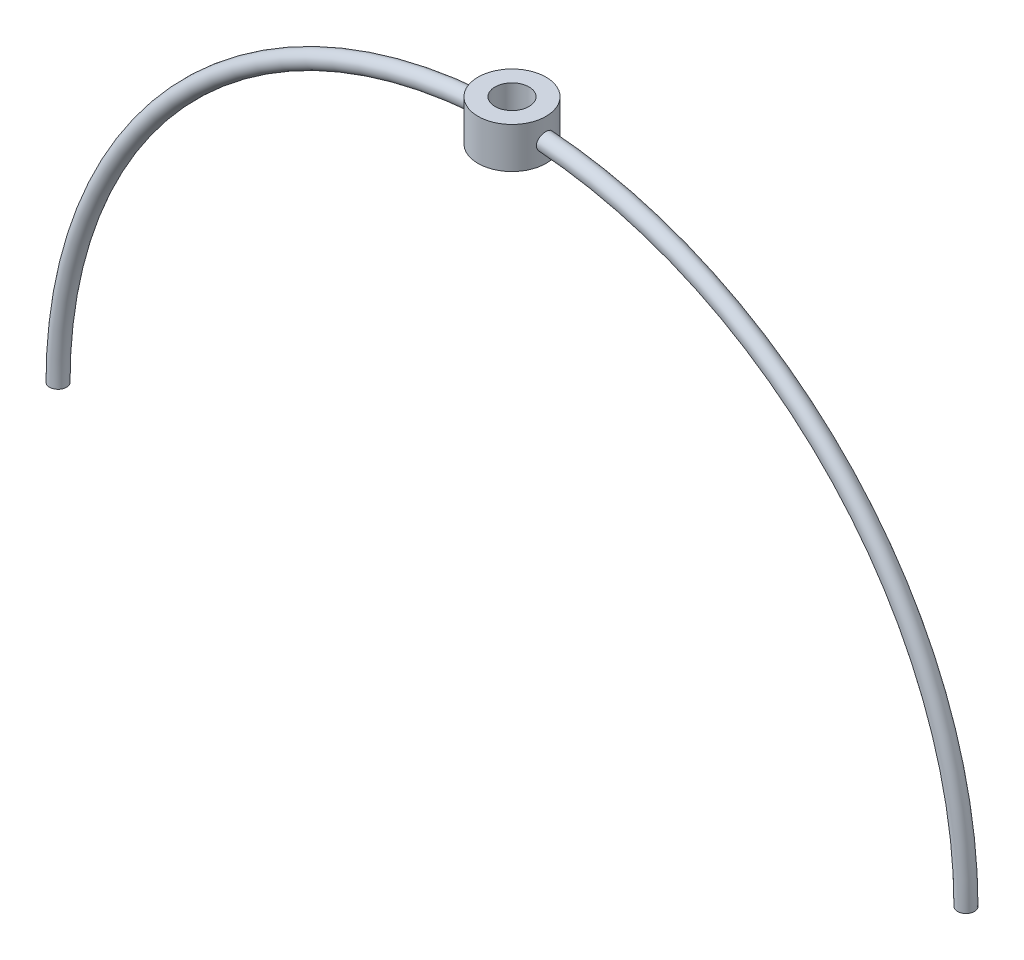
SolidWorks part; units mm, degrees
ref_plane "Front Plane" through (0, 0, 0) normal (0, 0, 1) x (1, 0, 0)
ref_plane "Top Plane" through (0, 0, 0) normal (0, 1, 0) x (1, 0, 0)
ref_plane "Right Plane" through (0, 0, 0) normal (1, 0, 0) x (0, 0, -1)
sketch "Sketch1" plane through (0, 0, 0) normal (0, 0, 1) x (1, 0, 0)
  line L0 (-507.5, -267) -> (-267, -267) construction
  line L1 (0, 185.9722) -> (0, -210.5278) construction
  arc A0 (-267, -267) -> (267, -267) centre (0, -267) cw
  dimension "D3" = 267
  dimension "D1" = 534
  dimension "D2" = 267
  dimension "D4" = 267
sketch "Sketch2" plane through (0, 0, 0) normal (1, 0, 0) x (0, 0, -1)
  circle A0 centre (0, 0) radius 3
  circle A1 centre (0, 0) radius 5
  dimension "D1" = 6
  dimension "D2" = 10
sweep "Sweep1" add profiles "Sketch2" path "Sketch1"
sketch "Sketch3" plane through (0, 0, 0) normal (0, 1, 0) x (1, 0, 0)
  circle A0 centre (0, 0) radius 20
  dimension "D1" = 40
extrude "Boss-Extrude1" add sketch "Sketch3" along normal blind 12 and the other way blind 12
sketch "Sketch4" plane through (0, 12, 0) normal (0, 1, 0) x (1, 0, 0)
  circle A0 centre (0, 0) radius 10
  dimension "D1" = 20
extrude "Cut-Extrude1" cut sketch "Sketch4" against normal blind 32
